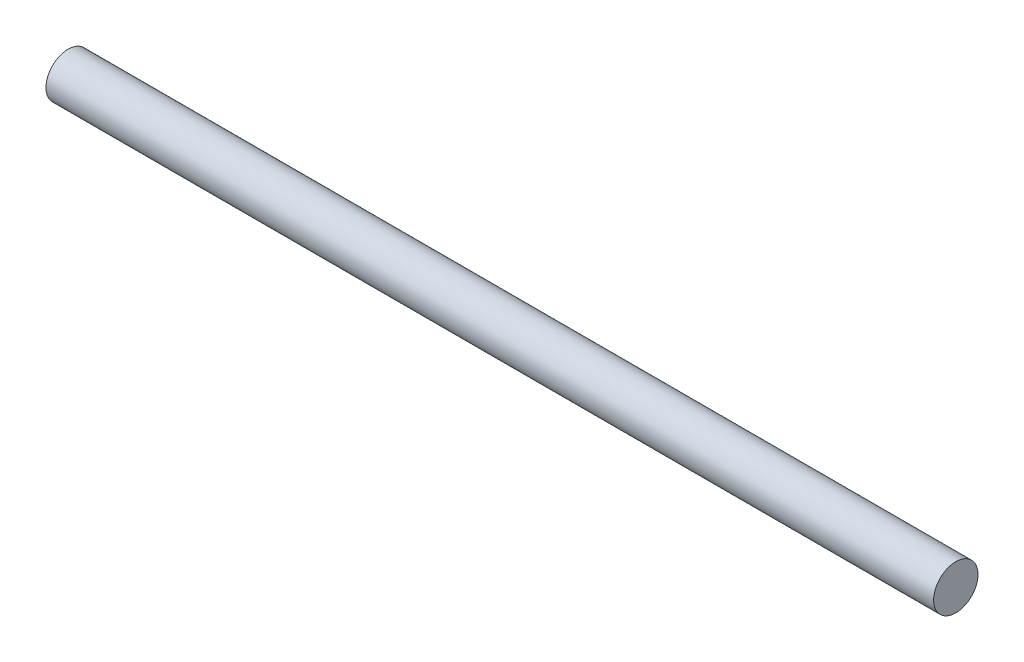
SolidWorks part; units mm, degrees
ref_plane "Front Plane" through (0, 0, 0) normal (0, 0, 1) x (1, 0, 0)
ref_plane "Top Plane" through (0, 0, 0) normal (0, 1, 0) x (1, 0, 0)
ref_plane "Right Plane" through (0, 0, 0) normal (1, 0, 0) x (0, 0, -1)
sketch "Sketch1" plane through (0, 0, 0) normal (1, 0, 0) x (0, 0, -1)
  circle A0 centre (0, 0) radius 3.175
  dimension "D1" = 6.35
extrude "Boss-Extrude1" add sketch "Sketch1" along normal mid plane 127
